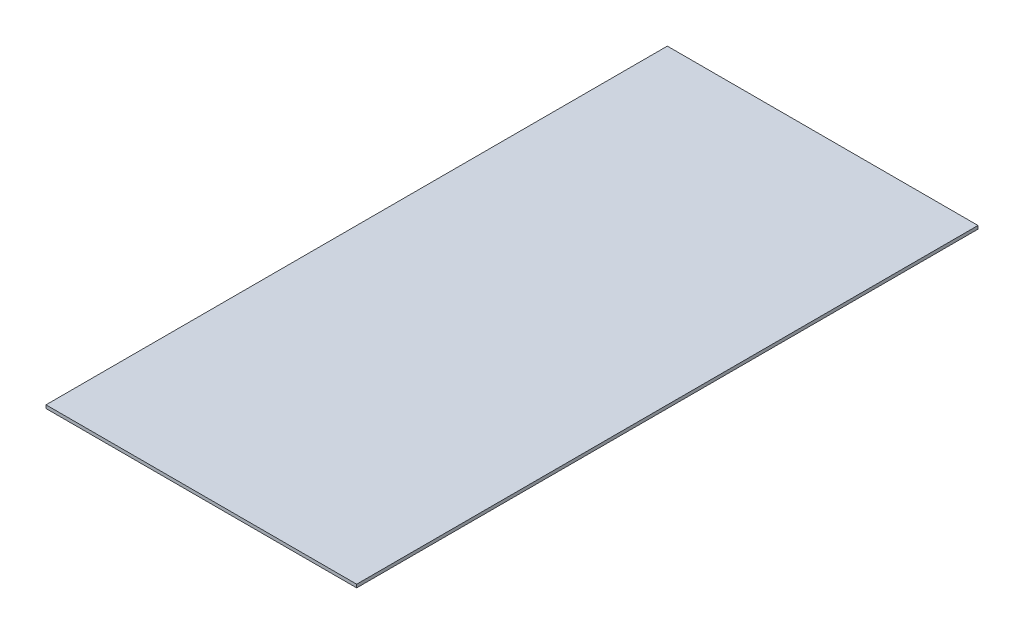
SolidWorks part; units mm, degrees
ref_plane "Front Plane" through (0, 0, 0) normal (0, 0, 1) x (1, 0, 0)
ref_plane "Top Plane" through (0, 0, 0) normal (0, 1, 0) x (1, 0, 0)
ref_plane "Right Plane" through (0, 0, 0) normal (1, 0, 0) x (0, 0, -1)
sketch "Sketch1" plane through (0, 0, 0) normal (0, 1, 0) x (1, 0, 0)
  line L1 (-609.6, 1219.2) -> (609.6, 1219.2)
  line L2 (-609.6, 1219.2) -> (-609.6, -1219.2)
  line L3 (-609.6, -1219.2) -> (609.6, -1219.2)
  line L4 (609.6, 1219.2) -> (609.6, -1219.2)
  line L5 (-609.6, 1219.2) -> (609.6, -1219.2) construction
  line L6 (-609.6, -1219.2) -> (609.6, 1219.2) construction
  point P0 (0, 0)
  dimension "D1" = 1219.2
  dimension "D2" = 2438.4
extrude "Boss-Extrude1" add sketch "Sketch1" along normal blind 12.7
